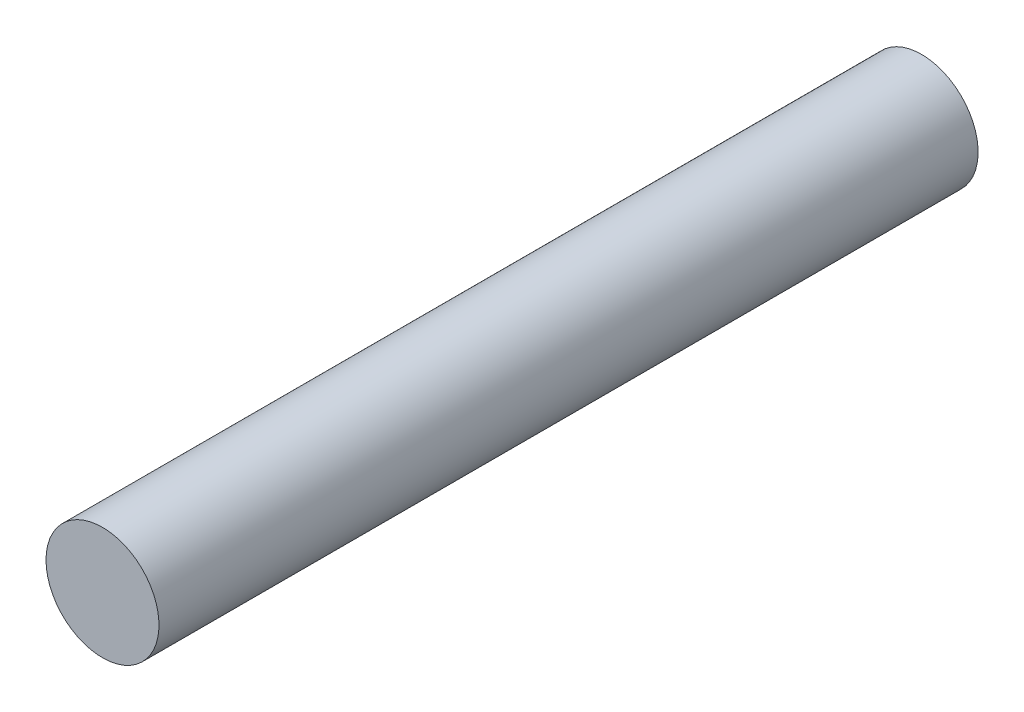
SolidWorks part; units mm, degrees
ref_plane "Front Plane" through (0, 0, 0) normal (0, 0, 1) x (1, 0, 0)
ref_plane "Top Plane" through (0, 0, 0) normal (0, 1, 0) x (1, 0, 0)
ref_plane "Right Plane" through (0, 0, 0) normal (1, 0, 0) x (0, 0, -1)
sketch "Sketch1" plane through (0, 0, 0) normal (0, 0, 1) x (1, 0, 0)
  circle A0 centre (0, 0) radius 4
  dimension "D1" = 8
extrude "Boss-Extrude1" add sketch "Sketch1" along normal mid plane 58
